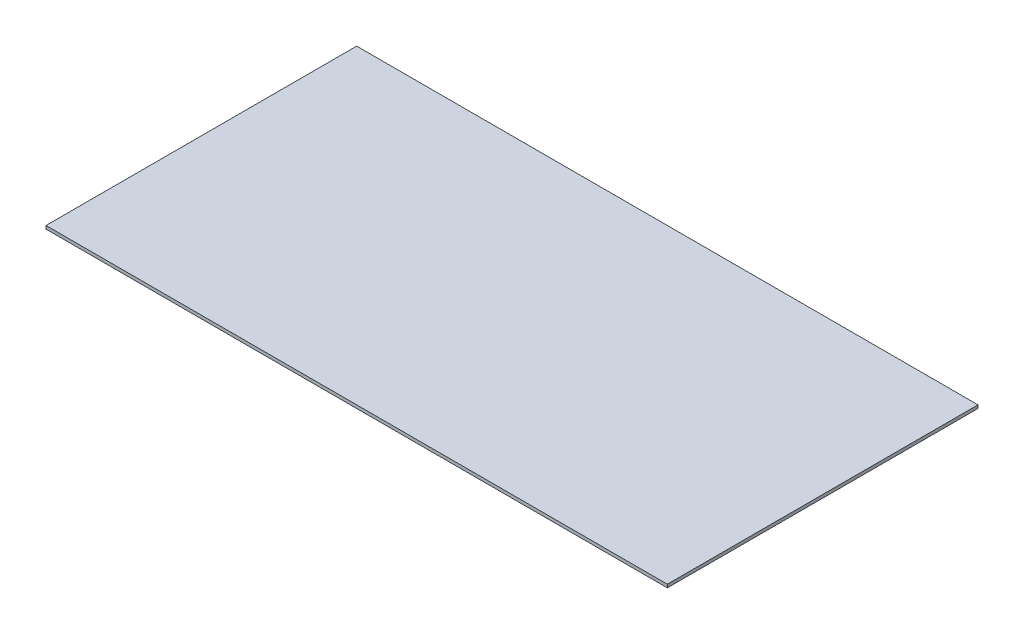
SolidWorks part; units mm, degrees
material "PC High Viscosity"
ref_plane "Front Plane" through (0, 0, 0) normal (0, 0, 1) x (1, 0, 0)
ref_plane "Top Plane" through (0, 0, 0) normal (0, 1, 0) x (1, 0, 0)
ref_plane "Right Plane" through (0, 0, 0) normal (1, 0, 0) x (0, 0, -1)
sketch "Sketch1" plane through (0, 0, 0) normal (0, 1, 0) x (1, 0, 0)
  line L1 (0, 0) -> (25.4, 0)
  line L2 (0, 0) -> (0, -12.7)
  line L3 (0, -12.7) -> (25.4, -12.7)
  line L4 (25.4, 0) -> (25.4, -12.7)
  dimension "D1" = 25.4
  dimension "D2" = 12.7
extrude "Boss-Extrude1" add sketch "Sketch1" along normal blind 0.13
